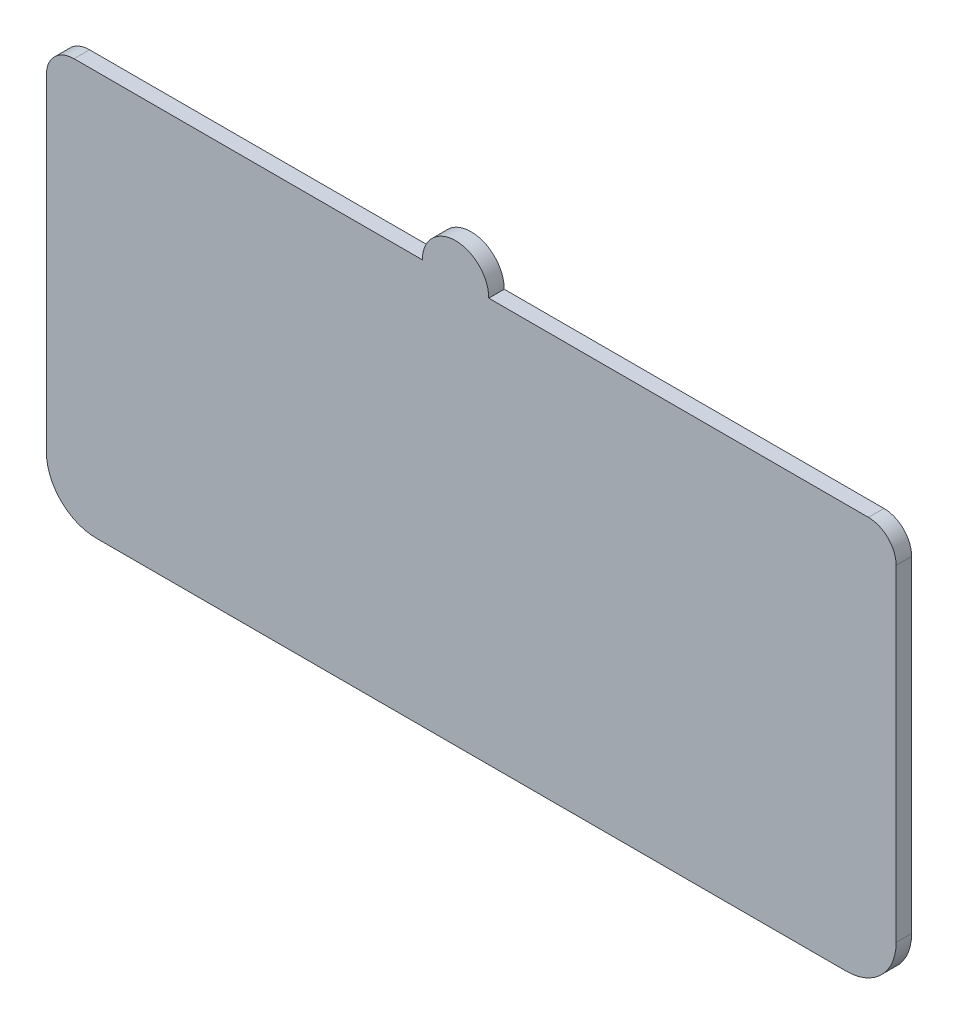
SolidWorks part; units mm, degrees
ref_plane "Front Plane" through (0, 0, 0) normal (0, 0, 1) x (1, 0, 0)
ref_plane "Top Plane" through (0, 0, 0) normal (0, 1, 0) x (1, 0, 0)
ref_plane "Right Plane" through (0, 0, 0) normal (1, 0, 0) x (0, 0, -1)
sketch "Sketch1" plane through (0, 0, 0) normal (0, 0, 1) x (1, 0, 0)
  line L0 (3.1633, 36.5) -> (76.75, 36.5)
  line L1 (-76.75, 36.5) -> (-8.8367, 36.5)
  line L2 (-76.75, 36.5) -> (-76.75, -36.5)
  line L3 (-76.75, -36.5) -> (76.75, -36.5)
  line L4 (76.75, 36.5) -> (76.75, -36.5)
  line L5 (-76.75, 36.5) -> (76.75, -36.5) construction
  line L6 (-76.75, -36.5) -> (76.75, 36.5) construction
  arc A0 (3.1633, 36.5) -> (-8.8367, 36.5) centre (-2.8367, 36.5) ccw
  point P0 (0, 0)
  dimension "D3" = 6
  dimension "D1" = 73
  dimension "D2" = 153.5
extrude "Boss-Extrude1" add sketch "Sketch1" along normal blind 2.8
fillet "Fillet1" radius 9 2 edges at (76.75, -36.5, 1.4) (-76.75, -36.5, 1.4)
fillet "Fillet2" radius 5 2 edges at (-76.75, 36.5, 1.4) (76.75, 36.5, 1.4)
